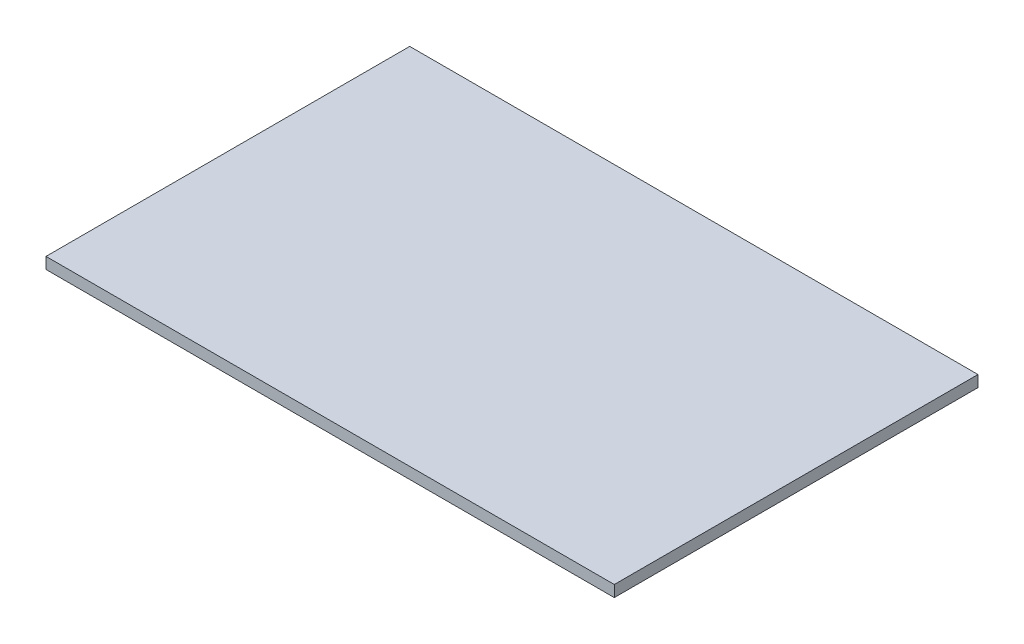
SolidWorks part; units mm, degrees
ref_plane "Front Plane" through (0, 0, 0) normal (0, 0, 1) x (1, 0, 0)
ref_plane "Top Plane" through (0, 0, 0) normal (0, 1, 0) x (1, 0, 0)
ref_plane "Right Plane" through (0, 0, 0) normal (1, 0, 0) x (0, 0, -1)
sketch "Sketch1" plane through (0, 0, 0) normal (0, 1, 0) x (1, 0, 0)
  line L1 (-79.375, -50.8) -> (79.375, -50.8)
  line L2 (-79.375, -50.8) -> (-79.375, 50.8)
  line L3 (-79.375, 50.8) -> (79.375, 50.8)
  line L4 (79.375, -50.8) -> (79.375, 50.8)
  line L5 (-79.375, -50.8) -> (79.375, 50.8) construction
  line L6 (-79.375, 50.8) -> (79.375, -50.8) construction
  point P0 (0, 0)
  dimension "D1" = 158.75
  dimension "D2" = 101.6
extrude "Boss-Extrude1" add sketch "Sketch1" along normal blind 3.175
